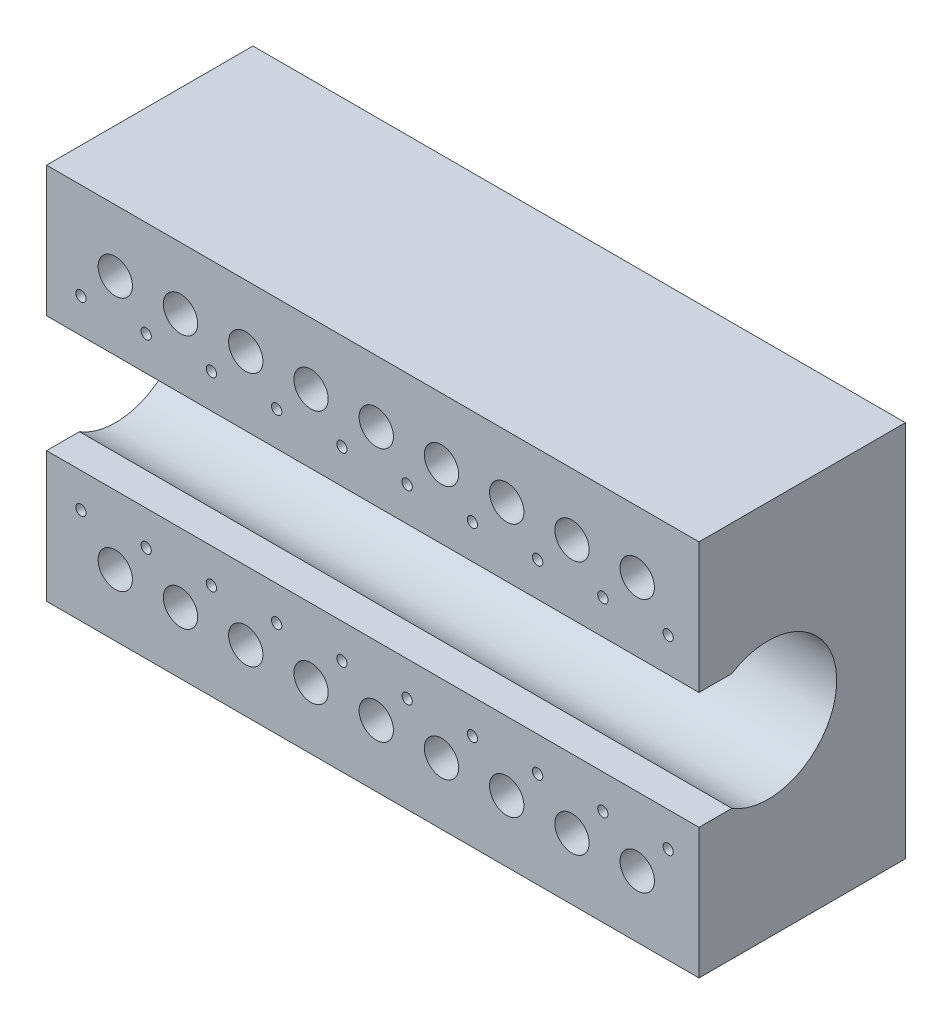
SolidWorks part; units mm, degrees
ref_plane "Front Plane" through (0, 0, 0) normal (0, 0, 1) x (1, 0, 0)
ref_plane "Top Plane" through (0, 0, 0) normal (0, 1, 0) x (1, 0, 0)
ref_plane "Right Plane" through (0, 0, 0) normal (1, 0, 0) x (0, 0, -1)
sketch "Sketch1" plane through (0, 0, 0) normal (1, 0, 0) x (0, 0, -1)
  line L1 (0, 0) -> (601, 0)
  line L2 (0, 0) -> (0, 1100)
  line L3 (0, 1100) -> (601, 1100)
  line L4 (601, 0) -> (601, 1100)
  circle A0 centre (201, 550) radius 200
  dimension "D3" = 400
  dimension "D5" = 400
  dimension "D1" = 1100
  dimension "D2" = 601
  dimension "D4" = 550
extrude "Boss-Extrude1" add sketch "Sketch1" along normal blind 1900
sketch "Sketch2" plane through (0, 0, 0) normal (0, 0, 1) x (1, 0, 0)
  line L0 (0, 1100) -> (0, 0) construction
  line L1 (0, 720) -> (1900, 720)
  line L2 (0, 720) -> (0, 380)
  line L3 (0, 380) -> (1900, 380)
  line L4 (1900, 720) -> (1900, 380)
  line L5 (1900, 1100) -> (0, 1100) construction
  dimension "D1" = 340
  dimension "D2" = 1900
  dimension "D3" = 0
  dimension "D4" = 380
extrude "Cut-Extrude1" cut sketch "Sketch2" against normal blind 300
sketch "Sketch3" plane through (0, 0, 0) normal (0, 0, 1) x (1, 0, 0)
  line L0 (1900, 720) -> (0, 720) construction
  line L1 (0, 1100) -> (0, 720) construction
  circle A0 centre (100, 820) radius 15
  circle A1 centre (200, 920) radius 50
  circle A2 centre (290, 820) radius 15
  circle A3 centre (480, 820) radius 15
  circle A4 centre (670, 820) radius 15
  circle A5 centre (860, 820) radius 15
  circle A6 centre (1050, 820) radius 15
  circle A7 centre (1240, 820) radius 15
  circle A8 centre (1430, 820) radius 15
  circle A9 centre (1620, 820) radius 15
  circle A10 centre (1810, 820) radius 15
  circle A11 centre (290, 280) radius 15
  circle A12 centre (480, 280) radius 15
  circle A13 centre (670, 280) radius 15
  circle A14 centre (860, 280) radius 15
  circle A15 centre (1050, 280) radius 15
  circle A16 centre (1240, 280) radius 15
  circle A17 centre (1430, 280) radius 15
  circle A18 centre (1620, 280) radius 15
  circle A19 centre (1810, 280) radius 15
  circle A20 centre (100, 280) radius 15
  circle A21 centre (390, 920) radius 50
  circle A22 centre (580, 920) radius 50
  circle A23 centre (770, 920) radius 50
  circle A24 centre (960, 920) radius 50
  circle A25 centre (1150, 920) radius 50
  circle A26 centre (1340, 920) radius 50
  circle A27 centre (1530, 920) radius 50
  circle A28 centre (1720, 920) radius 50
  circle A29 centre (390, 180) radius 50
  circle A30 centre (580, 180) radius 50
  circle A31 centre (770, 180) radius 50
  circle A32 centre (960, 180) radius 50
  circle A33 centre (1150, 180) radius 50
  circle A34 centre (1340, 180) radius 50
  circle A35 centre (1530, 180) radius 50
  circle A36 centre (1720, 180) radius 50
  circle A37 centre (200, 180) radius 50
  dimension "D2" = 30
  dimension "D3" = 100
  dimension "D8" = 100
  dimension "D9" = 9
  dimension "D1" = 100
  dimension "D4" = 200
  dimension "D5" = 200
  dimension "D6" = 10
  dimension "D7" = 2
  dimension "D10" = 2
extrude "Cut-Extrude2" cut sketch "Sketch3" against normal through all
sketch "Sketch4" plane through (0, 1100, 0) normal (0, 1, 0) x (1, 0, 0)
  line L0 (1900, 601) -> (0, 601) construction
  line L1 (120, 341) -> (370, 341)
  line L2 (120, 341) -> (120, 75)
  line L3 (120, 75) -> (370, 75)
  line L4 (370, 341) -> (370, 75)
  line L5 (1900, 0) -> (0, 0) construction
  line L6 (0, 601) -> (0, 0) construction
  dimension "D1" = 260
  dimension "D2" = 75
  dimension "D3" = 120
  dimension "D4" = 250
equation "\"D1@Cut-Extrude3\"=200"
